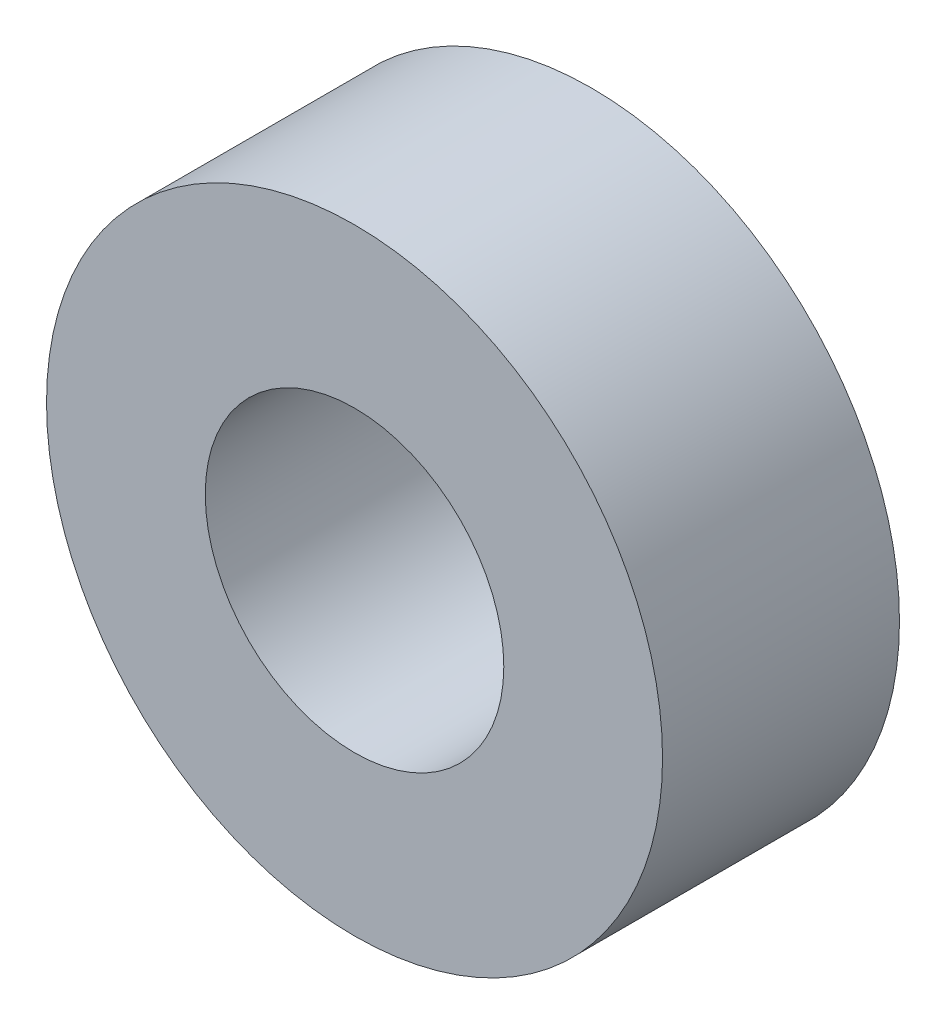
SolidWorks part; units mm, degrees
ref_plane "Front Plane" through (0, 0, 0) normal (0, 0, 1) x (1, 0, 0)
ref_plane "Top Plane" through (0, 0, 0) normal (0, 1, 0) x (1, 0, 0)
ref_plane "Right Plane" through (0, 0, 0) normal (1, 0, 0) x (0, 0, -1)
sketch "Sketch1" plane through (0, 0, 0) normal (0, 0, 1) x (1, 0, 0)
  circle A0 centre (0, 0) radius 6.5
  circle A1 centre (0, 0) radius 3.15
  dimension "OD" = 13
  dimension "ID" = 6.3
extrude "Extrude1" add sketch "Sketch1" along normal mid plane 5
sketch "Sketch2" plane through (0, 0, 0) normal (1, 0, 0) x (0, 0, -1)
  line L0 (-2.5, -3.15) -> (2.5, -3.15) construction
  line L3 (2.5, 3.15) -> (-2.5, 3.15) construction
  line L5 (-2.5, -3.15) -> (2.5, -3.15)
  line L6 (2.5, 3.15) -> (-2.5, 3.15)
sketch "Sketch4" plane through (0, 0, 2.5) normal (0, 0, 1) x (1, 0, 0)
  line L0 (0, 0) -> (-2.2274, 2.2274)
  line L1 (0, -1.1) -> (0, 1.1) construction
  circle A0 centre (0, 0) radius 3.15 construction
  dimension "D1" = 45
